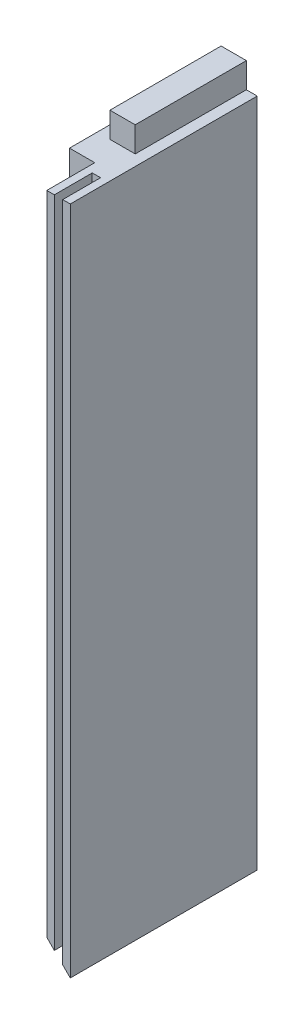
SolidWorks part; units mm, degrees
ref_plane "Front Plane" through (0, 0, 0) normal (0, 0, 1) x (1, 0, 0)
ref_plane "Top Plane" through (0, 0, 0) normal (0, 1, 0) x (1, 0, 0)
ref_plane "Right Plane" through (0, 0, 0) normal (1, 0, 0) x (0, 0, -1)
sketch "Sketch1" plane through (0, 0, 0) normal (0, 1, 0) x (1, 0, 0)
  line L0 (-41.8558, 39.3454) -> (-41.8558, -53.1594) construction
  line L12 (-51.5058, 37) -> (-51.5058, -18)
  line L13 (-32.2058, -37) -> (-32.2058, 37)
  line L14 (-35.2058, -37) -> (-32.2058, -37)
  line L15 (-35.2058, -22) -> (-35.2058, -37)
  line L16 (-38.5058, -22) -> (-35.2058, -22)
  line L17 (-38.5058, -37) -> (-38.5058, -22)
  line L18 (-41.5058, -37) -> (-38.5058, -37)
  line L19 (-41.5058, -18) -> (-41.5058, -37)
  line L20 (-51.5058, -18) -> (-41.5058, -18)
  line L21 (-32.2058, 37) -> (-51.5058, 37)
extrude "Boss-Extrude1" add sketch "Sketch1" along normal blind 265.3
sketch "Sketch2" plane through (0, 265.3, 0) normal (0, 1, 0) x (1, 0, 0)
  line L0 (-46.5058, 37) -> (-36.5058, 37)
  line L1 (-36.5058, 37) -> (-36.5058, -7)
  line L2 (-36.5058, -7) -> (-46.5058, -7)
  line L3 (-46.5058, -7) -> (-46.5058, 37)
  line L6 (-32.2058, -37) -> (-32.2058, 37) construction
  dimension "D1" = 44
  dimension "D2" = 10
  dimension "D3" = 4.3
extrude "Boss-Extrude2" add sketch "Sketch2" along normal blind 10
ref_plane "Plane3" through (-16.1029, -16.1029, 0) normal (-0.7071, -0.7071, 0) x (0, 0, -1)
sketch "Sketch3" plane through (-16.1029, -16.1029, 0) normal (-0.7071, -0.7071, 0) x (0, 0, -1)
  line L1 (-149.1166, 11.9645) -> (231.9937, 11.9645)
  line L2 (-149.1166, 11.9645) -> (-149.1166, -76.2811)
  line L3 (-149.1166, -76.2811) -> (231.9937, -76.2811)
  line L4 (231.9937, 11.9645) -> (231.9937, -76.2811)
  line L5 (-149.1166, 11.9645) -> (231.9937, -76.2811) construction
  line L6 (-149.1166, -76.2811) -> (231.9937, 11.9645) construction
  point P0 (41.4385, -32.1583)
extrude "Cut-Extrude1" cut sketch "Sketch3" along normal blind 27
sketch "Sketch4" plane through (-16.1029, -16.1029, 0) normal (-0.7071, -0.7071, 0) x (0, 0, 1)
  line L0 (18, 50.0673) -> (-37, 50.0673) construction
  line L1 (-25, 44.0673) -> (3, 44.0673)
  line L2 (-25, 44.0673) -> (-25, 37.0673)
  line L3 (-25, 37.0673) -> (3, 37.0673)
  line L4 (3, 44.0673) -> (3, 37.0673)
  line L5 (-37, 50.0673) -> (-37, 22.7729) construction
  dimension "D1" = 28
  dimension "D2" = 7
  dimension "D3" = 6
  dimension "D4" = 12
extrude "Boss-Extrude3" add sketch "Sketch4" along normal blind 7
